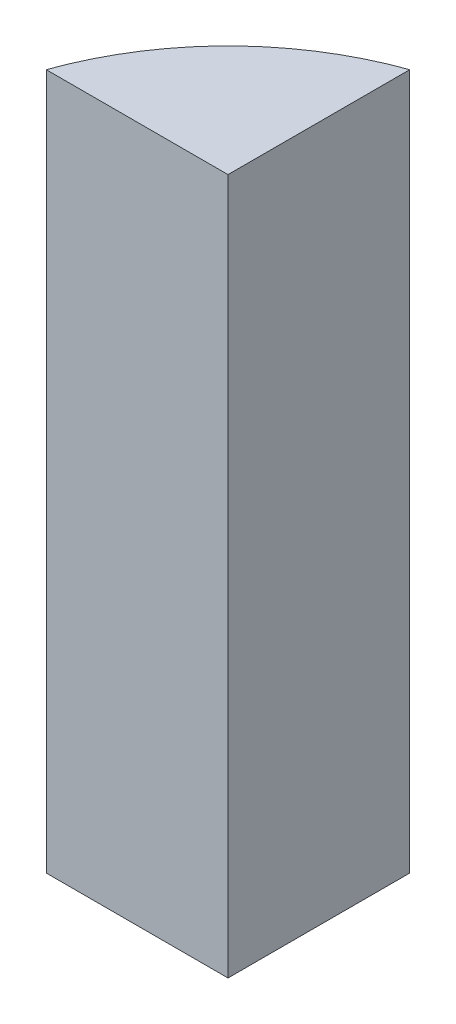
SolidWorks part; units mm, degrees
ref_plane "前视基准面" through (0, 0, 0) normal (0, 0, 1) x (1, 0, 0)
ref_plane "上视基准面" through (0, 0, 0) normal (0, 1, 0) x (1, 0, 0)
ref_plane "右视基准面" through (0, 0, 0) normal (1, 0, 0) x (0, 0, -1)
sketch "草图1" plane through (0, 0, 0) normal (0, 1, 0) x (1, 0, 0)
  line L0 (-56.5685, -20) -> (56.5685, -20)
  line L1 (-56.5685, 20) -> (56.5685, 20)
  line L2 (-20, 56.5685) -> (-20, -56.5685)
  line L3 (20, 56.5685) -> (20, -56.5685)
  circle A0 centre (0, 0) radius 60
  dimension "D1" = 120
  dimension "D2" = 20
  dimension "D3" = 20
  dimension "D4" = 20
  dimension "D5" = 20
extrude "凸台-拉伸1" add sketch "草图1" along normal blind 140 contours L2 A0 L1
